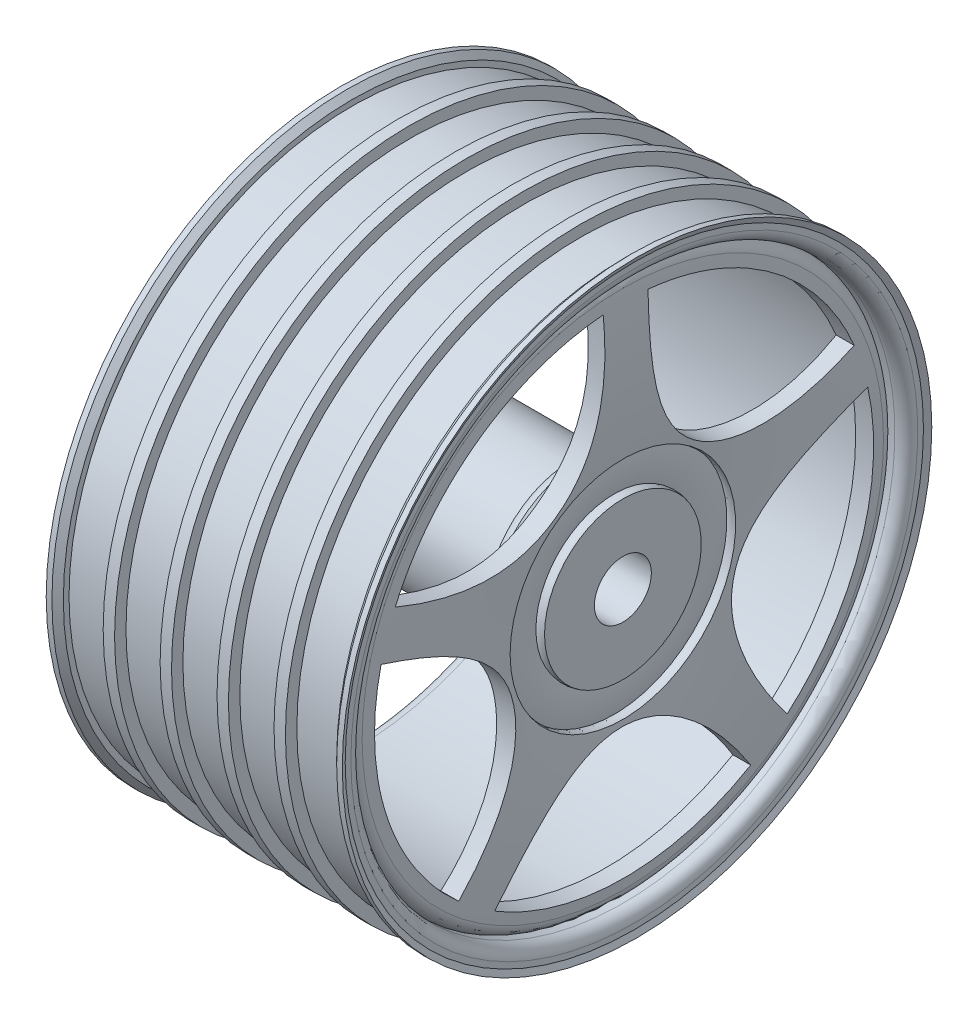
SolidWorks part; units mm, degrees
material "ПВХ Жесткий"
ref_plane "Спереди" through (0, 0, 0) normal (0, 0, 1) x (1, 0, 0)
ref_plane "Сверху" through (0, 0, 0) normal (0, 1, 0) x (1, 0, 0)
ref_plane "Справа" through (0, 0, 0) normal (1, 0, 0) x (0, 0, -1)
sketch "Эскиз10" plane through (0, 0, 0) normal (0, 0, 1) x (1, 0, 0)
  line L0 (0, 0) -> (-0.4873, 0.0059)
  line L1 (-0.4873, 0.0059) -> (-0.9882, -0.4972)
  line L2 (-0.9882, -0.4972) -> (-0.9882, -0.9986)
  line L3 (-0.9882, -0.9986) -> (-4.9882, -0.9986)
  line L4 (-4.9882, -0.9986) -> (-4.9882, 0.0041)
  line L5 (-4.9882, 0.0041) -> (-5.9884, 0.0041)
  line L6 (-5.9884, 0.0041) -> (-5.9884, -0.9986)
  line L7 (-5.9884, -0.9986) -> (-9.9884, -0.9986)
  line L8 (-9.9884, -0.9986) -> (-9.9956, 0)
  line L9 (-9.9956, 0) -> (-10.9958, 0)
  line L10 (-10.9958, 0) -> (-10.9958, -1.0027)
  line L11 (-10.9958, -1.0027) -> (-14.9958, -1.0027)
  line L12 (-14.9958, -1.0027) -> (-14.9912, 0.0007)
  line L13 (-14.9912, 0.0007) -> (-15.9912, 0.0007)
  line L14 (-15.9912, 0.0007) -> (-15.9912, -1.002)
  line L15 (-15.9912, -1.002) -> (-19.9912, -1.002)
  line L16 (-19.9912, -1.002) -> (-19.9912, 0.0007)
  line L17 (-19.9912, 0.0007) -> (-20.9912, 0.0007)
  line L18 (-20.9912, 0.0007) -> (-20.9912, -1.002)
  line L19 (-20.9912, -1.002) -> (-24.9912, -1.002)
  line L20 (-24.9912, -1.002) -> (-24.9912, -0.502)
  line L21 (-24.9912, -0.502) -> (-25.4932, 0)
  line L22 (-25.4932, 0) -> (-25.9932, 0)
  line L23 (-25.9932, 0) -> (-25.7459, -0.5)
  line L24 (-25.7459, -0.5) -> (-25.7459, -1)
  line L25 (-24.7459, -2) -> (-2.75, -2)
  line L26 (-14.9958, -25.8783) -> (-1.2434, -25.8783) construction
  line L27 (0, 0) -> (-0.2383, -0.4947)
  line L28 (-0.2383, -0.4947) -> (-0.2383, -0.9947)
  line L29 (-1.2434, -1.9933) -> (-2, -2)
  line L31 (-2.75, -2) -> (-2.75, -50002) construction
  line L36 (-1.2434, -19) -> (-1.2434, -25.8783)
  line L43 (-2.9801, -15.5837) -> (-5, -18)
  line L44 (-6, -19) -> (-24.7474, -19)
  line L45 (-24.7474, -19) -> (-24.7474, -23.9622)
  line L46 (-24.7474, -23.9622) -> (-14.9958, -23.9622)
  line L47 (-14.9958, -23.9622) -> (-14.9958, -25.8783)
  line L48 (-14.9958, -25.8783) -> (-1.2434, -25.8783)
  arc A0 (-25.7459, -1) -> (-24.7459, -2) centre (-24.7459, -1) ccw
  arc A1 (-0.2383, -0.9947) -> (-1.2434, -1.9933) centre (-1.2369, -0.9947) cw
  arc A2 (-2, -2) -> (-1.2498, -2.992) centre (-2.441, -3.1132) cw
  arc A3 (-2.9801, -15.5837) -> (-2.75, -4) centre (-43.2458, -8.9898) ccw
  arc A4 (-2.75, -4) -> (-2.75, -2) centre (5.3658, -3) cw
  arc A5 (-1.2498, -2.992) -> (-1.2434, -15.9783) centre (-85.8262, -9.527) cw
  arc A6 (-1.2434, -15.9783) -> (-2, -15.985) centre (-1.6303, -15.013) cw
  arc A7 (-5, -18) -> (-6, -19) centre (-5, -19) ccw
  arc A8 (-1.2434, -19) -> (-2.0004, -19) centre (-1.6219, -19.9686) ccw
  arc A9 (-2, -15.985) -> (-2.0004, -19) centre (-10.1885, -17.4913) cw
  point P74 (-1.2498, -2.992)
  point P109 (-14.9958, -23.9622)
  point P110 (-14.9958, -25.8783)
  dimension "D1" = 25.9932
revolve "Повернуть1" add sketch "Эскиз10" angle 360 about L26
sketch "Эскиз11" plane through (0, 0, 0) normal (1, 0, 0) x (0, 0, -1)
  arc A0 (-1.793, -4.0788) -> (-20.0559, -17.1804) centre (0.0419, -25.9161) ccw
  arc A4 (20.2434, -17.4229) -> (2.1395, -4.1025) centre (0.0419, -25.9161) ccw
  arc A5 (14.362, -42.5043) -> (21.4361, -21.1703) centre (0.0419, -25.9161) ccw
  arc A6 (-11.3093, -44.6614) -> (11.1666, -44.7967) centre (0.0419, -25.9161) ccw
  arc A7 (-21.2936, -20.9131) -> (-14.4768, -42.3308) centre (0.0419, -25.9161) ccw
  spline S0 degree 3 poles (20.2434, -17.4229) (13.8382, -19.8038) (4.5358, -19.8783) (1.8514, -10.8096) (2.1395, -4.1025) knots 0.063206 0.063206 0.063206 0.063206 0.515766 0.95719 0.95719 0.95719 0.95719
  spline S1 degree 3 poles (14.362, -42.5043) (10.1184, -37.1484) (7.1729, -28.3243) (14.9682, -22.9689) (21.4361, -21.1703) knots 0.063206 0.063206 0.063206 0.063206 0.515766 0.95719 0.95719 0.95719 0.95719
  spline S2 degree 3 poles (-11.3093, -44.6614) (-7.5268, -38.9704) (-0.0448, -33.4423) (7.4573, -39.2012) (11.1666, -44.7967) knots 0.063206 0.063206 0.063206 0.063206 0.515766 0.95719 0.95719 0.95719 0.95719
  spline S3 degree 3 poles (-21.2936, -20.9131) (-14.7123, -22.7518) (-7.1427, -28.1594) (-10.3014, -37.0739) (-14.4768, -42.3308) knots 0.063206 0.063206 0.063206 0.063206 0.515766 0.95719 0.95719 0.95719 0.95719
  spline S5 degree 3 poles (-1.793, -4.0788) (-1.508, -10.9062) (-4.3117, -19.7764) (-13.7661, -19.527) (-20.0559, -17.1804) knots 0.063206 0.063206 0.063206 0.063206 0.515766 0.95719 0.95719 0.95719 0.95719
  point P18 (0.0419, -25.9161)
  point P36 (0, -25.8783)
  dimension "D1" = 5
extrude "Вырез-Вытянуть2" cut sketch "Эскиз11" against normal blind 10 contours S5 A0 | S3 A7 | S2 A6 | S1 A5 | S0 A4
sketch "Эскиз12" plane through (-1.2434, 0, 0) normal (1, 0, 0) x (0, 0, -1)
  circle A0 centre (0, -25.8783) radius 2.5
extrude "Вырез-Вытянуть3" cut sketch "Эскиз12" against normal blind 100
